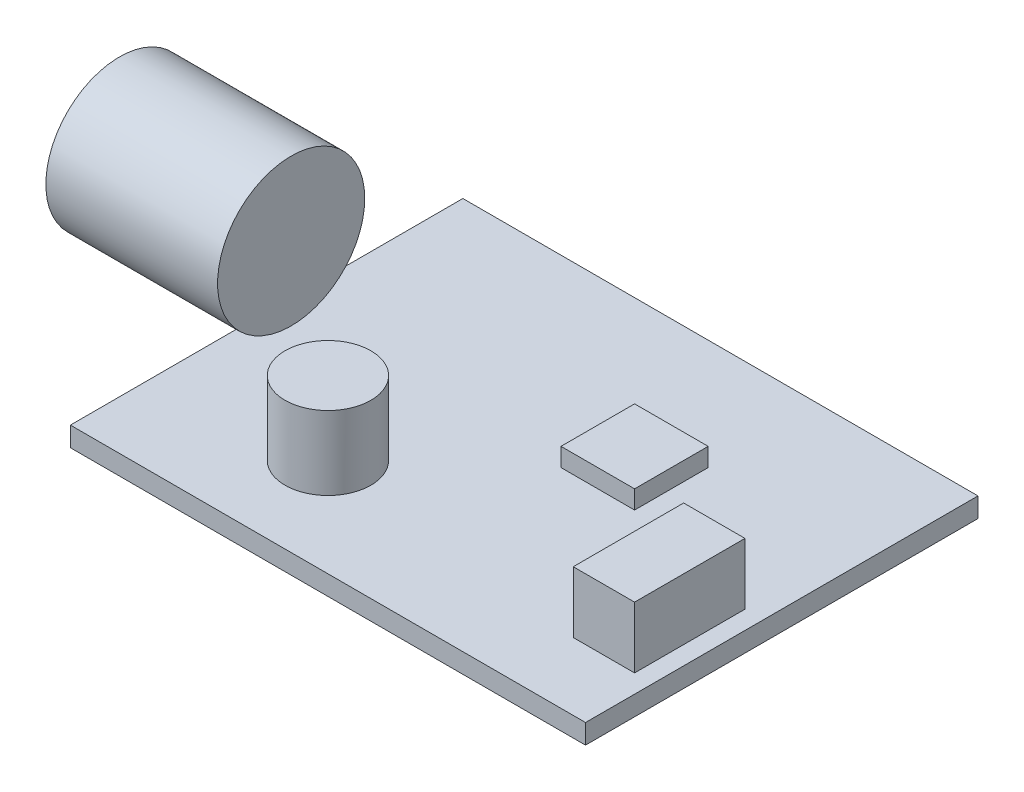
SolidWorks part; units mm, degrees
ref_plane "Front Plane" through (0, 0, 0) normal (0, 0, 1) x (1, 0, 0)
ref_plane "Top Plane" through (0, 0, 0) normal (0, 1, 0) x (1, 0, 0)
ref_plane "Right Plane" through (0, 0, 0) normal (1, 0, 0) x (0, 0, -1)
other "Configuration Table"
sketch "Sketch1" plane through (0, 0, 0) normal (0, 1, 0) x (1, 0, 0)
  line L1 (-21, -16) -> (21, -16)
  line L2 (-21, -16) -> (-21, 16)
  line L3 (-21, 16) -> (21, 16)
  line L4 (21, -16) -> (21, 16)
  line L5 (-21, -16) -> (21, 16) construction
  line L6 (-21, 16) -> (21, -16) construction
extrude "PCB" add sketch "Sketch1" along normal blind 1.6
sketch "Sketch2" plane through (0, 0, 0) normal (0, 1, 0) x (1, 0, 0)
  line L1 (2, 1) -> (8, 1)
  line L2 (2, 1) -> (2, 7)
  line L3 (2, 7) -> (8, 7)
  line L4 (8, 1) -> (8, 7)
  line L5 (2, 1) -> (8, 7) construction
  line L6 (2, 7) -> (8, 1) construction
extrude "IC" add sketch "Sketch2" along normal blind 1.5 from offset 1.6
sketch "Sketch3" plane through (0, 0, 0) normal (0, 1, 0) x (1, 0, 0)
  line L1 (14.5, -10.5) -> (19.5, -10.5)
  line L2 (14.5, -10.5) -> (14.5, -1.5)
  line L3 (14.5, -1.5) -> (19.5, -1.5)
  line L4 (19.5, -10.5) -> (19.5, -1.5)
  line L5 (14.5, -10.5) -> (19.5, -1.5) construction
  line L6 (14.5, -1.5) -> (19.5, -10.5) construction
extrude "Out_Connector" add sketch "Sketch3" along normal blind 5 from offset 1.6
sketch "Sketch4" plane through (0, 0, 0) normal (1, 0, 0) x (0, 0, -1)
  circle A0 centre (0, 7.6) radius 6
extrude "BNC_Socket" add sketch "Sketch4" along normal blind 14 from offset 33
sketch "Sketch5" plane through (0, 0, 0) normal (0, 1, 0) x (1, 0, 0)
  circle A0 centre (-8, -8) radius 3.5
extrude "Trim_Pot" add sketch "Sketch5" along normal blind 6 from offset 1.6
equation "\"sig_L\"= 42.0   'ASSUMPTION: TDS / ORP signal board L (NOT in PDF table - designer guess)"
equation "\"sig_W\"= 32.0   'ASSUMPTION: TDS / ORP signal board W (NOT in PDF table - designer guess)"
equation "\"pcb_t\"= 1.6   'ASSUMPTION: PCB thickness (standard)"
equation "\"D1@PCB\" = \"pcb_t\""
